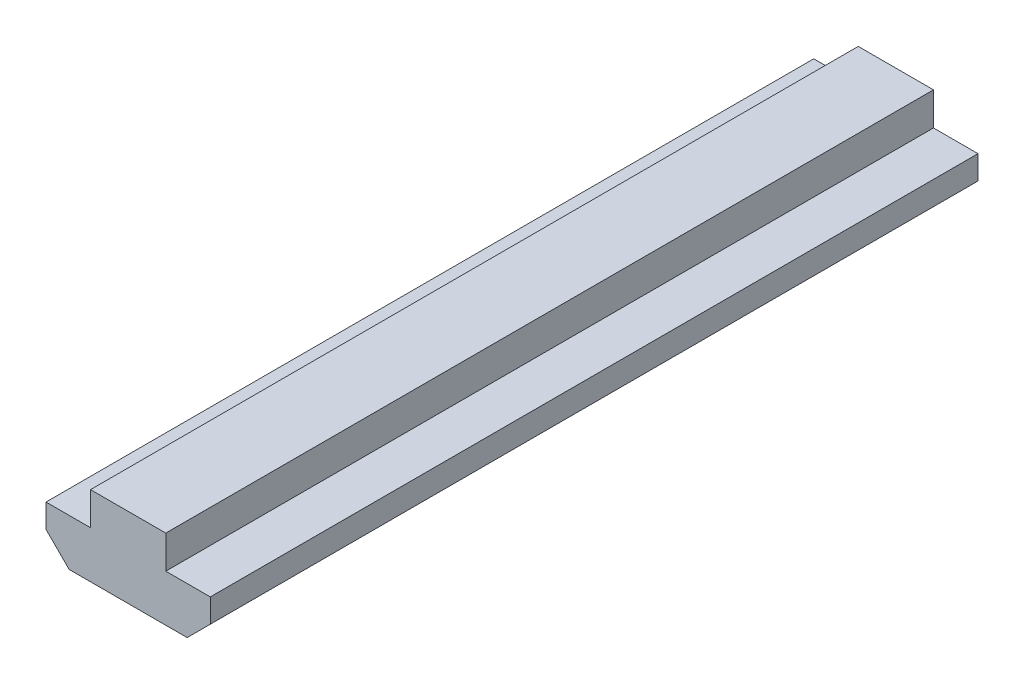
SolidWorks part; units mm, degrees
ref_plane "前视基准面" through (0, 0, 0) normal (0, 0, 1) x (1, 0, 0)
ref_plane "上视基准面" through (0, 0, 0) normal (0, 1, 0) x (1, 0, 0)
ref_plane "右视基准面" through (0, 0, 0) normal (1, 0, 0) x (0, 0, -1)
sketch "草图1" plane through (0, 0, 0) normal (0, 0, 1) x (1, 0, 0)
  line B0 (15.6, 4.3) -> (15.6, 0)
  line B1 (5.8, 4.3) -> (5.8, 0)
  line B2 (3.015, -6.1) -> (18.385, -6.1)
  line B3 (5.8, 4.3) -> (15.6, 4.3)
  line B4 (0, 0) -> (5.8, 0)
  line B5 (15.6, 0) -> (21.4, 0)
  line B6 (18.385, -6.1) -> (21.4, -3.085)
  line B7 (3.015, -6.1) -> (0, -3.085)
  line B8 (0, -3.085) -> (0, 0)
  line B9 (21.4, -3.085) -> (21.4, 0)
sketch_block_instance "A$C14247EC1-1"
sketch_block "A$C14247EC1"
extrude "凸台-拉伸1" add sketch "草图1" along normal blind 100
